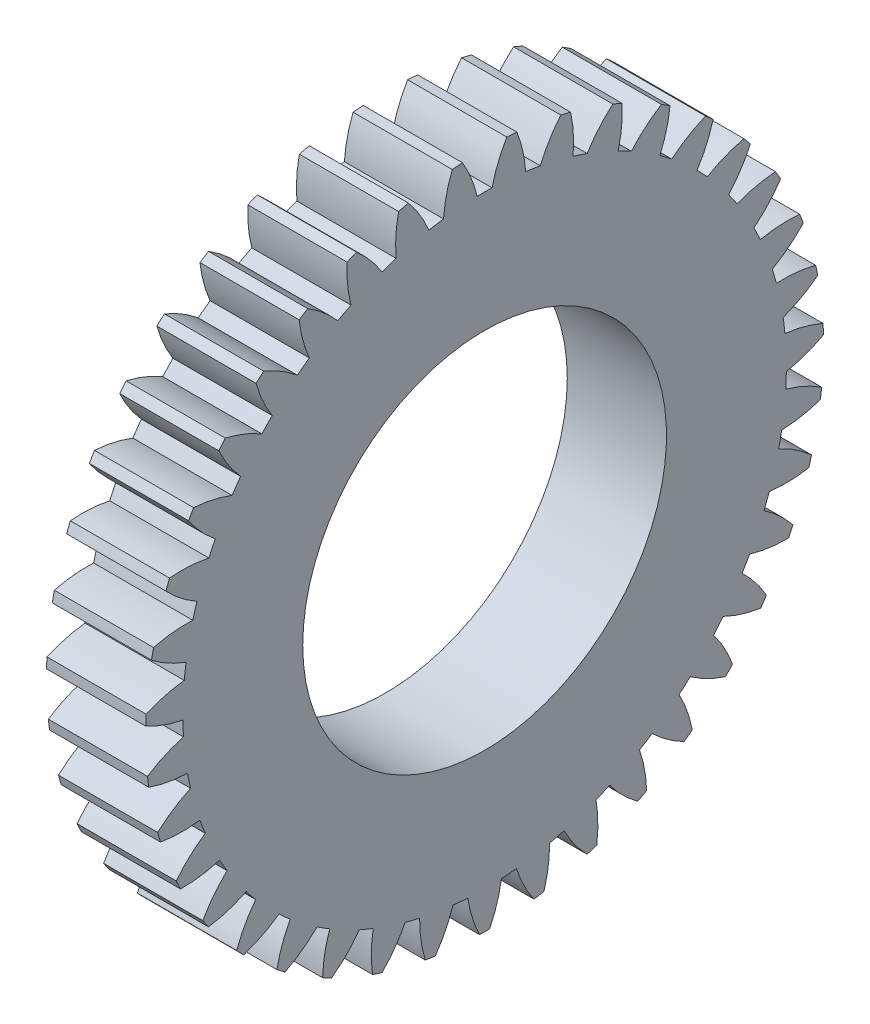
SolidWorks part; units mm, degrees
ref_plane "Plane1" through (0, 0, 0) normal (0, 0, 1) x (1, 0, 0)
ref_plane "Plane2" through (0, 0, 0) normal (0, 1, 0) x (1, 0, 0)
ref_plane "Plane3" through (0, 0, 0) normal (1, 0, 0) x (0, 0, -1)
other "Configuration Table"
sketch "HoldingSke" plane through (0, 0, 0) normal (0, 1, 0) x (1, 0, 0)
  line L0 (0, 0) -> (0.7771, -0.6293)
  line L1 (-15, 0) -> (100, 0) construction
  line L2 (0, 0) -> (-2.1039, 2.3779)
  line L3 (0, 0) -> (-11.863, 4.5341)
  line L4 (0, 0) -> (6.7114, 5.4348)
  line L5 (0, 0) -> (-46.8476, -17.4728)
  line L6 (0, 0) -> (-4.9738, -3.3558)
  line L7 (-2.1039, 2.3779) -> (8.6586, 51.2059)
  line L8 (-76.2, 54.61) -> (-72.9, 54.61)
  line L9 (-71.009, 38.7566) -> (-53.1078, 45.2721)
  line L10 (-76.2, 71.12) -> (104.1128, 71.12)
  line L11 (0, 0) -> (-6, 0)
  line L12 (-76.2, 101.6) -> (-76.162, 101.6)
  line L13 (24.9733, 27.94) -> (52.9518, 28.4284)
  line L14 (24.9733, 27.94) -> (24.9743, 27.94)
  line L15 (24.9733, 27.94) -> (100.4006, 29.5858)
  line L16 (-63.627, -1) -> (-12.827, -1)
  circle A0 centre (0, 0) radius 11
  circle A1 centre (0, 0) radius 18.249
  circle A2 centre (0, 0) radius 37.5
  circle A3 centre (0, 0) radius 11
  dimension "MHD" = 36.498
  dimension "Hub_dia" = 75
  dimension "Bore" = 22
  dimension "MBD" = 22
  dimension "Num_teeth" = 39
  dimension "Pitch" = 1
  dimension "Overall_len" = 50
  dimension "Show_teeth" = 39
  dimension "Thickness" = 6
  dimension "OAL" = 50.0001
  dimension "T_dim" = 3.3
  dimension "Ap" = 20
  dimension "H" = 19.05
  dimension "Pitch_radius" = 180.3128
  dimension "Width" = 6
  dimension "Backlash" = 0.038
  dimension "Addendum_fac" = 1
  dimension "Dedendum_fac" = 1.25
  dimension "Clearance_fac" = 0.25
  dimension "Dedendum_add" = 0.001
  dimension "Module" = 1
sketch "BasProSke" plane through (0, 0, 0) normal (0, 1, 0) x (1, 0, 0)
  line L0 (-10, 0) -> (60, 0) construction
  line L1 (0, 0) -> (0, 20.5)
  line L2 (0, 0) -> (6, 0)
  line L3 (6, 0) -> (6, 20.5)
  line L4 (6, 20.5) -> (0, 20.5)
  dimension "Thickness" = 6
  dimension "Diameter" = 41
revolve "Base-Revolve" add sketch "BasProSke" angle 360 about L0
sketch "TooCutSke" plane through (0, 0, 0) normal (1, 0, 0) x (0, 0, -1)
  line L1 (0, 0) -> (0, 107) construction
  line L2 (0, 0) -> (-0.8517, 19.4814) construction
  line L3 (0, 0) -> (-3.1361, 38.8471) construction
  line L4 (-0.8517, 19.4814) -> (-1.568, 19.4236) construction
  arc A0 (0.4501, 18.2434) -> (-0.4501, 18.2434) centre (0, 0) ccw
  arc A1 (1.358, 20.4804) -> (-1.358, 20.4804) centre (0, 0) ccw
  circle A2 centre (0, 0) radius 19.5 construction
  circle A3 centre (0, 0) radius 18.324 construction
  arc A4 (-0.4501, 18.2434) -> (-1.358, 20.4804) centre (-8.0443, 16.4638) ccw
  arc A5 (1.358, 20.4804) -> (0.4501, 18.2434) centre (8.0443, 16.4638) ccw
  dimension "Root_dia" = 36.498
  dimension "Overcut_dia" = 41.0508
  dimension "Pitch_dia" = 39
  dimension "Base_dia" = 36.648
  dimension "Flank_rad" = 7.8
  dimension "Half_ang" = 4.615
  dimension "Half_CT" = 0.7187
extrude "ToothCut" cut sketch "TooCutSke" along normal through all
fillet "Breaks" [suppressed] radius 0.02
fillet "RootFillets" [suppressed] radius 0.251
pattern_circular "TeethCuts" count 39 every 9.231 about axis through (-10, 0, 0) along (1, 0, 0) of "ToothCut", "RootFillets", "Breaks"
sketch "HubNeaOneSke" plane through (0, 0, 0) normal (-1, 0, 0) x (0, 0, 1)
  circle A0 centre (0, 0) radius 18.249
  dimension "Diameter" = 36.498
extrude "HubNearOne" [suppressed] add sketch "HubNeaOneSke" along normal blind 44.0001
sketch "HubNeaBotSke" plane through (0, 0, 0) normal (-1, 0, 0) x (0, 0, 1)
  circle A0 centre (0, 0) radius 18.249
  dimension "Diameter" = 36.498
extrude "HubNearBoth" [suppressed] add sketch "HubNeaBotSke" along normal blind 22
ref_plane "FarPln" through (6, 0, 0) normal (1, 0, 0) x (0, 0, -1)
sketch "HubFarSke" plane through (6, 0, 0) normal (1, 0, 0) x (0, 0, -1)
  circle A0 centre (0, 0) radius 18.249
  dimension "Diameter" = 36.498
extrude "HubFar" [suppressed] add sketch "HubFarSke" along normal blind 22
sketch "BorSke" plane through (0, 0, 0) normal (1, 0, 0) x (0, 0, -1)
  circle A0 centre (0, 0) radius 11
  dimension "Diameter" = 22
extrude "Bore" cut sketch "BorSke" along normal mid plane 100.0001
sketch "KeySke" plane through (0, 0, 0) normal (1, 0, 0) x (0, 0, -1)
  line L0 (-4, 0) -> (-4, 14.3)
  line L1 (-4, 14.3) -> (4, 14.3)
  line L2 (4, 14.3) -> (4, 0)
  line L3 (0, 0) -> (0, 34) construction
  line L4 (-4, 0) -> (4, 0)
  dimension "Offset" = 14.3
  dimension "Width" = 8
extrude "Keyway" [suppressed] cut sketch "KeySke" along normal mid plane 100.0001
pattern_circular "Keyway2" [suppressed] count 2 every 90 about axis through (-10, 0, 0) along (1, 0, 0)
equation "' \"Module@HoldingSke\" = 6.35"
equation "' \"Num_teeth@HoldingSke\" = 12"
equation "' \"Ap@HoldingSke\" =  20"
equation "' \"Ap@HoldingSke\" = 20"
equation "' \"Width@HoldingSke\" = 0.5 * 25.4"
equation "' \"Hub_dia@HoldingSke\"= 1 * 25.4"
equation "' \"Hub_dia@HoldingSke\" = 1 * 25.4"
equation "' \"Overall_len@HoldingSke\" = 1.0 * 25.4"
equation "' \"Bore@HoldingSke\" = 0.75 * 25.4"
equation "' \"T_dim@HoldingSke\" = 0.1 * 25.4"
equation "' \"Width@KeySke\" = 0.25 * 25.4"
equation "' \"Show_teeth@HoldingSke\" = 13"
equation "' \"Backlash@HoldingSke\" = 0.009 * 25.4"
equation "' \"Addendum_fac@HoldingSke\" = 1.0"
equation "' \"Dedendum_fac@HoldingSke\" = 1.25"
equation "' \"Dedendum_add@HoldingSke\" = 0.00005 * 25.4"
equation "' \"Clearance_fac@HoldingSke\" = 0.25"
equation "\"Pitch@HoldingSke\" = 1 / \"Module@HoldingSke\""
equation "\"Overcut_dia@TooCutSke\" = (\"Num_teeth@HoldingSke\" + 2 * \"Addendum_fac@HoldingSke\") / \"Pitch@HoldingSke\" + 0.002 * 25.4"
equation "\"Pitch_dia@TooCutSke\" = \"Num_teeth@HoldingSke\" / \"Pitch@HoldingSke\""
equation "\"Base_dia@TooCutSke\" = \"Num_teeth@HoldingSke\" / \"Pitch@HoldingSke\" * cos((\"Ap@HoldingSke\"  * 3.14159265 / 180))"
equation "\"Root_dia@TooCutSke\" = (\"Num_teeth@HoldingSke\" + 2) / \"Pitch@HoldingSke\" - 2 * (\"Addendum_fac@HoldingSke\" + \"Dedendum_fac@HoldingSke\") / \"Pitch@HoldingSke\" - \"Dedendum_add@HoldingSke\" * 2"
equation "\"Half_ang@TooCutSke\" = 180 / \"Num_teeth@HoldingSke\""
equation "\"Half_CT@TooCutSke\" = \"Num_teeth@HoldingSke\" / \"Pitch@HoldingSke\" * sin((3.14159265 / 2 / \"Num_teeth@HoldingSke\")) / 2 - 7 * \"Backlash@HoldingSke\" / 4"
equation "\"Flank_rad@TooCutSke\" = \"Num_teeth@HoldingSke\" / \"Pitch@HoldingSke\" / 5"
equation "\"Radius@RootFillets\" = \"Clearance_fac@HoldingSke\" / \"Pitch@HoldingSke\" + \"Dedendum_add@HoldingSke\""
equation "\"Break_rad@Breaks\" = 0.02 / \"Pitch@HoldingSke\""
equation "\"Thickness@HoldingSke\" = \"Width@HoldingSke\""
equation "\"OAL@HoldingSke\" = \"Thickness@HoldingSke\""
equation "\"MHD@HoldingSke\" = (\"Num_teeth@HoldingSke\" + 2) / \"Pitch@HoldingSke\" - 2 * (\"Addendum_fac@HoldingSke\" + \"Dedendum_fac@HoldingSke\")  / \"Pitch@HoldingSke\" - \"Dedendum_add@HoldingSke\" * 2"
equation "\"MBD@HoldingSke\" = (\"Num_teeth@HoldingSke\" + 2) / \"Pitch@HoldingSke\" - 2 * (\"Addendum_fac@HoldingSke\" + \"Dedendum_fac@HoldingSke\")  / \"Pitch@HoldingSke\" - \"Dedendum_add@HoldingSke\" * 2 - 0.002 * 25.4"
equation "\"MHD@HoldingSke\" = ((sgn( \"MHD@HoldingSke\" - \"Hub_dia@HoldingSke\" )-1)*( \"MHD@HoldingSke\" - \"Hub_dia@HoldingSke\" ))/-2+ \"Hub_dia@HoldingSke\""
equation "\"MBD@HoldingSke\" = ((sgn( \"MBD@HoldingSke\" - \"Bore@HoldingSke\" )-1)*( \"MBD@HoldingSke\" - \"Bore@HoldingSke\" ))/-2+ \"Bore@HoldingSke\""
equation "\"OAL@HoldingSke\" = ((sgn( \"OAL@HoldingSke\" - \"Overall_len@HoldingSke\" )+1)*( \"OAL@HoldingSke\" - \"Overall_len@HoldingSke\" ))/2 + \"Overall_len@HoldingSke\" + 0.000002 * 25.4"
equation "\"Num_teeth@TeethCuts\" = int( \"Show_teeth@HoldingSke\" ) + 1"
equation "\"Num_teeth@TeethCuts\" = ((sgn( \"Num_teeth@TeethCuts\" - \"Num_teeth@HoldingSke\" )-1)*( \"Num_teeth@TeethCuts\" - \"Num_teeth@HoldingSke\" ))/-2+ \"Num_teeth@HoldingSke\""
equation "\"Num_teeth@TeethCuts\" = ((sgn( \"Num_teeth@TeethCuts\" - 2.0)+1)*( \"Num_teeth@TeethCuts\" - 2.0))/2 +2.0"
equation "\"Angle@TeethCuts\" = 360.0 / \"Num_teeth@HoldingSke\""
equation "\"Diameter@BasProSke\" = (\"Num_teeth@HoldingSke\" + 2 * \"Addendum_fac@HoldingSke\") / \"Pitch@HoldingSke\""
equation "\"Thickness@BasProSke\"  = \"Thickness@HoldingSke\""
equation "' \"Fillet_rad@BasProSke\" =  \"Thickness@HoldingSke\" * 0.05"
equation "' \"Fillet_rad@BasProSke\" = \"Thickness@HoldingSke\" * 0.05"
equation "\"MHD@HoldingSke\" = ((sgn( \"MHD@HoldingSke\" - \"Root_dia@TooCutSke\" )-1)*( \"MHD@HoldingSke\" - \"Root_dia@TooCutSke\" ))/-2+ \"Root_dia@TooCutSke\""
equation "\"Diameter@HubNeaOneSke\" = \"MHD@HoldingSke\""
equation "\"Length@HubNearOne\" = \"OAL@HoldingSke\" - \"Thickness@BasProSke\""
equation "\"Diameter@HubNeaBotSke\" = \"MHD@HoldingSke\""
equation "\"Length@HubNearBoth\" = ( \"OAL@HoldingSke\" - \"Thickness@BasProSke\" ) / 2.0"
equation "\"Thickness@FarPln\" = \"Thickness@BasProSke\""
equation "\"Diameter@HubFarSke\" = \"MHD@HoldingSke\""
equation "\"Length@HubFar\" = ( \"OAL@HoldingSke\" - \"Thickness@BasProSke\" ) / 2.0"
equation "\"Diameter@BorSke\" = \"MBD@HoldingSke\""
equation "\"D1@Bore\" = \"OAL@HoldingSke\" * 2.0"
equation "\"D1@Keyway\" = \"OAL@HoldingSke\" * 2.0"
equation "\"Offset@KeySke\" = \"T_dim@HoldingSke\" + \"MBD@HoldingSke\" / 2.0"
